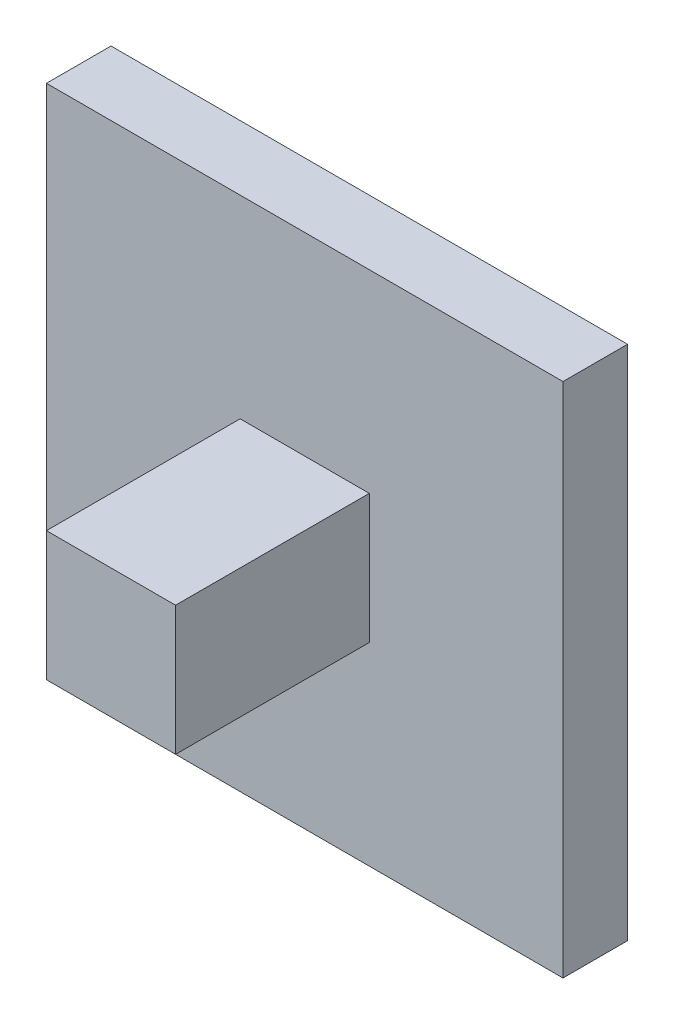
SolidWorks part; units mm, degrees
ref_plane "Plan de face" through (0, 0, 0) normal (0, 0, 1) x (1, 0, 0)
ref_plane "Plan de dessus" through (0, 0, 0) normal (0, 1, 0) x (1, 0, 0)
ref_plane "Plan de droite" through (0, 0, 0) normal (1, 0, 0) x (0, 0, -1)
sketch "Esquisse1" plane through (0, 0, 0) normal (0, 0, 1) x (1, 0, 0)
  line L1 (0, 0) -> (16, 0)
  line L2 (0, 0) -> (0, 16)
  line L3 (0, 16) -> (16, 16)
  line L4 (16, 0) -> (16, 16)
  dimension "D1" = 16
  dimension "D2" = 16
extrude "Boss.-Extru.1" add sketch "Esquisse1" along normal blind 2
sketch "Esquisse2" plane through (0, 0, 2) normal (0, 0, 1) x (1, 0, 0)
  line L0 (16, 0) -> (16, 16) construction
  line L1 (6, 6) -> (10, 6)
  line L2 (6, 6) -> (6, 10)
  line L3 (6, 10) -> (10, 10)
  line L4 (10, 6) -> (10, 10)
  line L5 (16, 16) -> (0, 16) construction
  point P6 (8, 16)
  dimension "D1" = 4
  dimension "D2" = 4
  dimension "D3" = 6
  dimension "D4" = 6
extrude "Boss.-Extru.2" add sketch "Esquisse2" along normal blind 6
